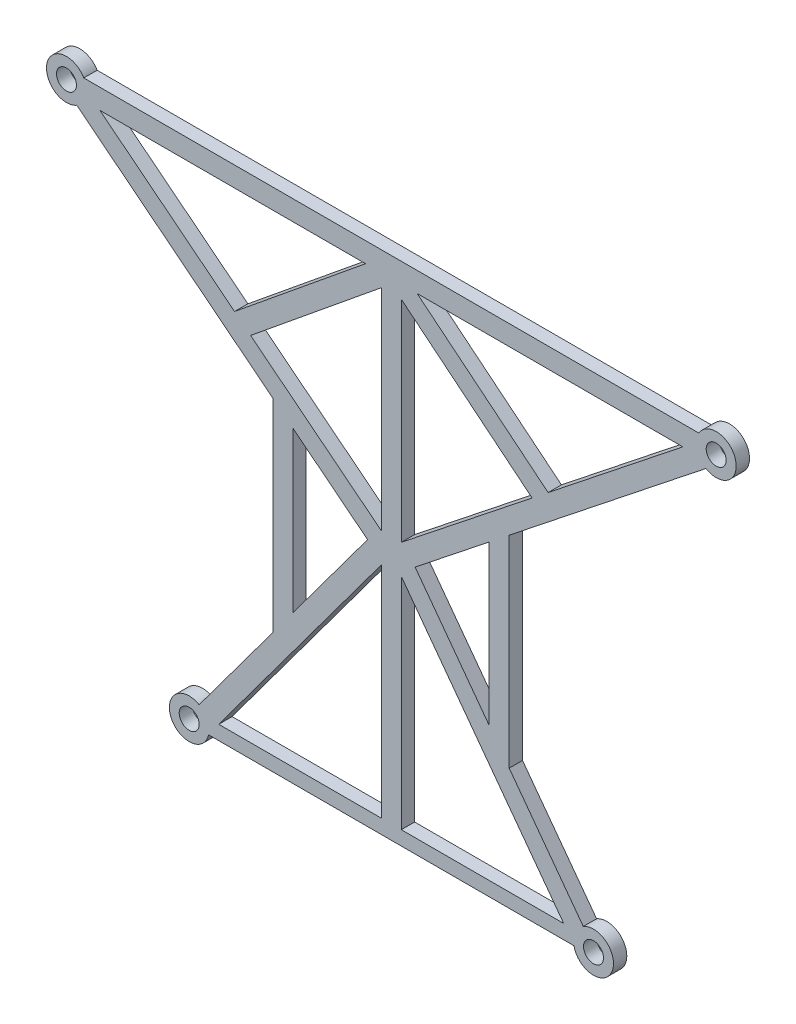
SolidWorks part; units mm, degrees
ref_plane "Plano frontal" through (0, 0, 0) normal (0, 0, 1) x (1, 0, 0)
ref_plane "Plano superior" through (0, 0, 0) normal (0, 1, 0) x (1, 0, 0)
ref_plane "Plano direito" through (0, 0, 0) normal (1, 0, 0) x (0, 0, -1)
sketch "Esboço1" plane through (0, 0, 0) normal (0, 0, 1) x (1, 0, 0)
  line L2 (-67.4749, 4.9471) -> (24.8289, 4.9471)
  line L5 (-48.7523, -71.0529) -> (6.0789, -71.0529)
  line L20 (-25.1955, 1.9471) -> (-44.8508, -14.0928)
  line L21 (4.5482, -68.926) -> (-19.823, -68.926)
  line L22 (-17.4505, 1.9471) -> (22.4159, 1.9471)
  line L23 (-22.823, 0.011) -> (-22.823, -31.5745)
  line L25 (-19.823, 0.0111) -> (-19.823, -31.5745)
  line L27 (-65.062, 1.9471) -> (-25.1955, 1.9471)
  line L28 (-22.823, -68.926) -> (-47.2244, -68.926)
  line L29 (-19.823, 0.0111) -> (-0.2004, -16.0016)
  line L31 (-22.823, 0.011) -> (-42.4453, -16.0019)
  line L32 (7.4815, -67.8462) -> (-3.6364, -52.8304)
  line L34 (25.8875, 0.8722) -> (-3.6364, -22.5584)
  line L35 (-68.5335, 0.8722) -> (-39.0945, -22.4911)
  line L36 (-24.8924, -33.7622) -> (-36.0945, -48.874)
  line L37 (4.5482, -68.926) -> (-19.823, -36.0102)
  line L38 (22.4159, 1.9471) -> (2.2051, -14.0925)
  line L39 (-65.062, 1.9471) -> (-44.8508, -14.0928)
  line L40 (-21.3228, -33.9846) -> (-21.323, -33.9848)
  line L41 (-0.2004, -16.0016) -> (-19.823, -31.5745)
  line L42 (-39.0945, -52.921) -> (-50.2966, -68.0328)
  line L43 (-17.4505, 1.9471) -> (2.2051, -14.0925)
  line L44 (-6.6364, -48.7785) -> (-17.7543, -33.7627)
  line L45 (-36.0945, -48.874) -> (-36.0945, -24.872)
  line L47 (-42.4453, -16.0019) -> (-22.823, -31.5745)
  line L49 (-3.6364, -52.8304) -> (-3.6364, -22.5584)
  line L50 (-39.0945, -52.921) -> (-39.0945, -22.4911)
  line L51 (-6.6364, -48.7785) -> (-6.6364, -24.9393)
  line L52 (-22.823, -36.0083) -> (-22.823, -68.926)
  line L54 (-21.323, -33.9843) -> (-21.323, -33.9848)
  line L55 (-19.823, -36.0102) -> (-19.823, -68.926)
  line L57 (-36.0945, -24.872) -> (-24.8924, -33.7622)
  line L58 (-6.6364, -24.9393) -> (-17.7543, -33.7627)
  line L59 (-22.823, -36.0083) -> (-47.2244, -68.926)
  line L60 (-21.3228, -33.9846) -> (-21.323, -33.9843)
  circle A0 centre (-70.073, 3.4471) radius 1.5
  circle A1 centre (27.427, 3.4471) radius 1.5
  circle A6 centre (9.0127, -70.426) radius 1.5
  circle A7 centre (-51.6587, -70.426) radius 1.5
  arc A9 (-67.4749, 4.9471) -> (-68.5335, 0.8722) centre (-70.073, 3.4471) ccw
  arc A10 (25.8875, 0.8722) -> (24.8289, 4.9471) centre (27.427, 3.4471) ccw
  arc A11 (6.0789, -71.0529) -> (7.4815, -67.8462) centre (9.0127, -70.426) ccw
  arc A12 (-50.165, -67.8552) -> (-48.7523, -71.0529) centre (-51.6587, -70.426) ccw
  dimension "D2" = 3
  dimension "D3" = 3
  dimension "D9" = 3
  dimension "D12" = 3
  dimension "D1" = 97.5
extrude "Ressalto-extrusão1" add sketch "Esboço1" along normal blind 2
